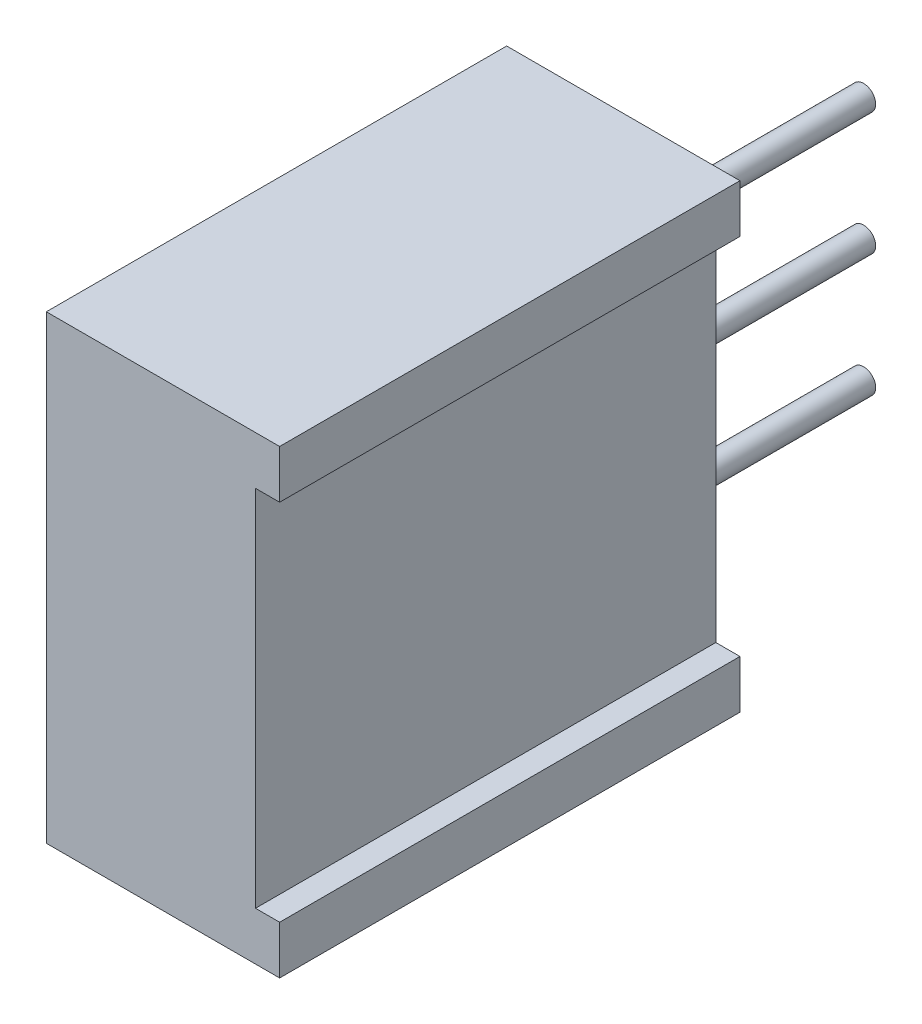
SolidWorks part; units mm, degrees
ref_plane "Front Plane" through (0, 0, 0) normal (0, 0, 1) x (1, 0, 0)
ref_plane "Top Plane" through (0, 0, 0) normal (0, 1, 0) x (1, 0, 0)
ref_plane "Right Plane" through (0, 0, 0) normal (1, 0, 0) x (0, 0, -1)
sketch "Sketch1" plane through (0, 0, 0) normal (1, 0, 0) x (0, 0, 1)
  line L0 (0, 0) -> (9.53, 0)
  line L1 (0, 0) -> (0, 9.53)
  line L2 (9.53, 9.53) -> (0, 9.53)
  line L3 (9.53, 9.53) -> (9.53, 0)
  dimension "D1" = 9.53
extrude "Basic Shape" add sketch "Sketch1" along normal blind 4.83
sketch "Sketch5" plane through (0, -19.06, 0) normal (0, 0, -1) x (0, -1, 0)
  line L0 (-9.53, 0) -> (-19.06, 0) construction
  line L2 (-19.06, -4.83) -> (-9.53, -4.83) construction
  circle A0 centre (-16.835, -2.39) radius 0.25
  circle A1 centre (-14.295, -2.39) radius 0.25
  circle A2 centre (-11.755, -2.39) radius 0.25
  point P8 (-14.295, 0)
  point P10 (0, 0)
  point P13 (0, 0)
  point P14 (0, 0)
  dimension "D4" = 0.5
  dimension "D1" = 2.44
  dimension "D3" = 2.54
  dimension "D5" = 2.54
extrude "Pins" add sketch "Sketch5" along normal blind 5
sketch "Sketch6" plane through (0, 0, 9.53) normal (0, 0, 1) x (1, 0, 0)
  line L0 (4.83, 0) -> (4.83, -9.53) construction
  line L3 (4.33, -8.53) -> (4.33, -1)
  line L4 (4.83, -1) -> (0, -1)
  line L5 (4.33, -1) -> (4.83, -1)
  line L6 (4.83, -8.53) -> (0, -8.53)
  line L7 (4.33, -8.53) -> (4.83, -8.53)
  line L9 (4.83, -8.53) -> (4.83, -1)
  dimension "D1" = 0.5
  dimension "D2" = 1
  dimension "D3" = 1
extrude "Rear Relief" cut sketch "Sketch6" against normal through all
ref_plane "Board Plane" through (0, 0, -1) normal (0, 0, 1) x (1, 0, 0)
sketch "Component_Outline" plane through (0, 0, -1) normal (0, 0, 1) x (1, 0, 0)
  line L0 (0, 0) -> (0, -9.53)
  line L1 (0, -9.53) -> (4.83, -9.53)
  line L2 (4.83, -9.53) -> (4.83, -8.53)
  line L3 (4.83, -8.53) -> (4.33, -8.53)
  line L4 (4.33, -8.53) -> (4.33, -1)
  line L5 (4.33, -1) -> (4.83, -1)
  line L6 (4.83, -1) -> (4.83, 0)
  line L7 (4.83, 0) -> (0, 0)
